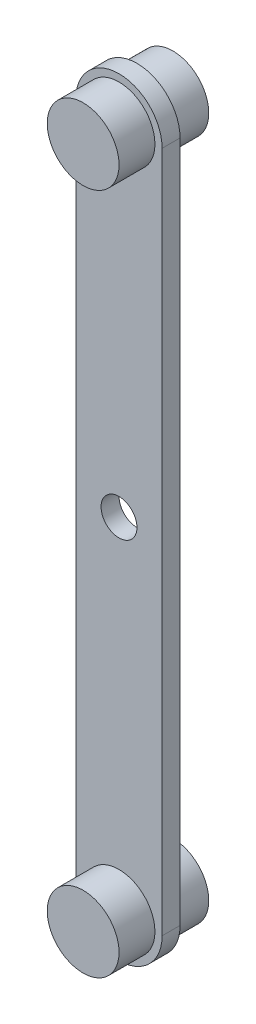
SolidWorks part; units mm, degrees
ref_plane "Front Plane" through (0, 0, 0) normal (0, 0, 1) x (1, 0, 0)
ref_plane "Top Plane" through (0, 0, 0) normal (0, 1, 0) x (1, 0, 0)
ref_plane "Right Plane" through (0, 0, 0) normal (1, 0, 0) x (0, 0, -1)
sketch "Sketch1" plane through (0, 0, 0) normal (0, 0, 1) x (1, 0, 0)
  line L0 (0, 0) -> (0, 210) construction
  line L1 (10, 10) -> (10, 200)
  line L2 (-10, 200) -> (-10, 10)
  arc A1 (10, 200) -> (-10, 200) centre (0, 200) ccw
  arc A2 (10, 10) -> (-10, 10) centre (0, 10) cw
  dimension "D2" = 10
  dimension "D1" = 210
extrude "Boss-Extrude1" add sketch "Sketch1" along normal blind 5
sketch "Sketch2" plane through (0, 0, 5) normal (0, 0, 1) x (1, 0, 0)
  circle A0 centre (0, 200) radius 10
  circle A1 centre (0, 10) radius 10
extrude "Boss-Extrude2" add sketch "Sketch2" along normal blind 10
sketch "Sketch3" plane through (0, 0, 0) normal (0, 0, -1) x (-1, 0, 0)
  line L0 (0, 200) -> (0, 10) construction
  circle A0 centre (0, 105) radius 5
extrude "Cut-Extrude1" cut sketch "Sketch3" against normal blind 10
sketch "Sketch4" plane through (0, 0, 0) normal (0, 0, -1) x (-1, 0, 0)
  circle A0 centre (0, 200) radius 10
  circle A1 centre (0, 10) radius 10
extrude "Boss-Extrude3" add sketch "Sketch4" along normal blind 10
sketch "Sketch5" plane through (0, 0, 0) normal (0, 0, -1) x (-1, 0, 0)
  line L0 (12, 200) -> (12, 10)
  line L1 (-12, 10) -> (-12, 200)
  arc A0 (12, 200) -> (-12, 200) centre (0, 200) ccw
  arc A1 (-12, 10) -> (12, 10) centre (0, 10) ccw
extrude "Boss-Extrude4" add sketch "Sketch5" against normal blind 5
sketch "Sketch9" plane through (0, 0, 0) normal (0, 0, -1) x (-1, 0, 0)
  line L0 (0, 200) -> (0, 10) construction
  circle A0 centre (0, 105) radius 5
extrude "Cut-Extrude4" cut sketch "Sketch9" against normal blind 35
